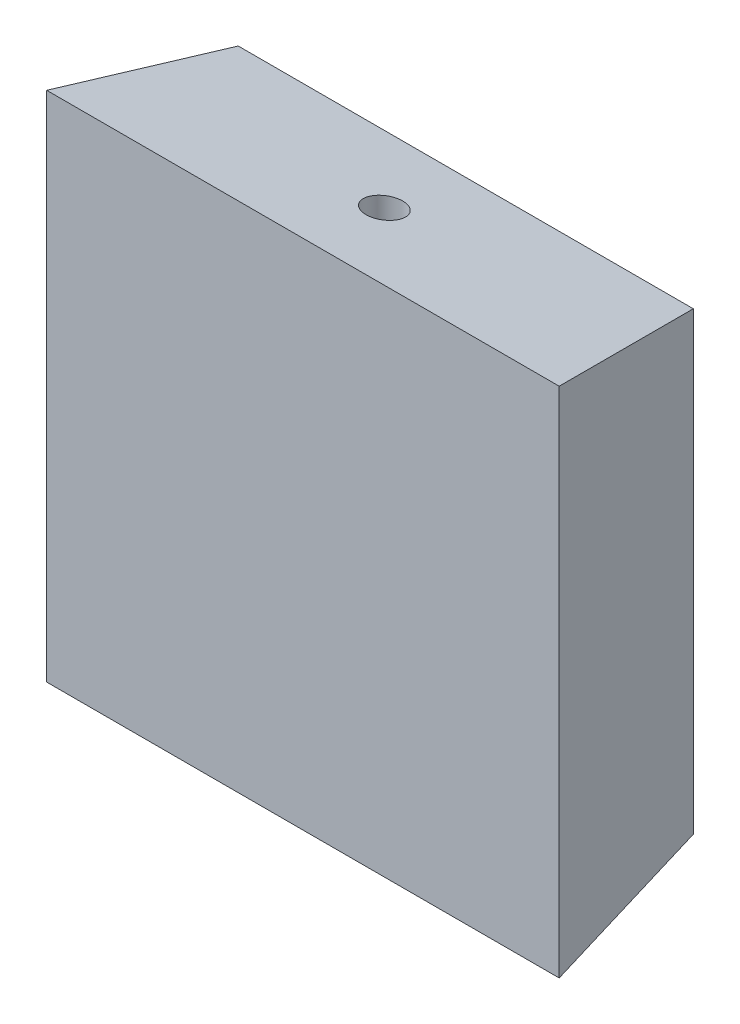
SolidWorks part; units mm, degrees
ref_plane "Plan de face" through (0, 0, 0) normal (0, 0, 1) x (1, 0, 0)
ref_plane "Plan de dessus" through (0, 0, 0) normal (0, 1, 0) x (1, 0, 0)
ref_plane "Plan de droite" through (0, 0, 0) normal (1, 0, 0) x (0, 0, -1)
sketch "Esquisse1" plane through (0, 0, 0) normal (0, 0, 1) x (1, 0, 0)
  line L1 (-20.701, -20.701) -> (20.701, -20.701)
  line L2 (-20.701, -20.701) -> (-20.701, 20.701)
  line L3 (-20.701, 20.701) -> (20.701, 20.701)
  line L4 (20.701, -20.701) -> (20.701, 20.701)
  line L5 (-20.701, -20.701) -> (20.701, 20.701) construction
  line L6 (-20.701, 20.701) -> (20.701, -20.701) construction
  point P0 (0, 0)
  dimension "D1" = 41.402
  dimension "D2" = 41.402
extrude "Boss.-Extru.1" add sketch "Esquisse1" along normal blind 14.8158 draft 10 draft outward yes
ref_plane "Plan1" through (0, 25.4, 0) normal (0, 1, 0) x (1, 0, 0)
sketch "Esquisse2" plane through (0, 25.4, 0) normal (0, 1, 0) x (1, 0, 0)
  line L0 (-20.701, 0) -> (0, 0)
  line L1 (20.701, 0) -> (-20.701, 0) construction
  line L2 (0, 0) -> (0, -7.4079)
  circle A0 centre (0, -7.4079) radius 1.6669
  dimension "D1" = 3.3337
extrude "Enlèv. mat.-Extru.1" cut sketch "Esquisse2" against normal blind 12.7
